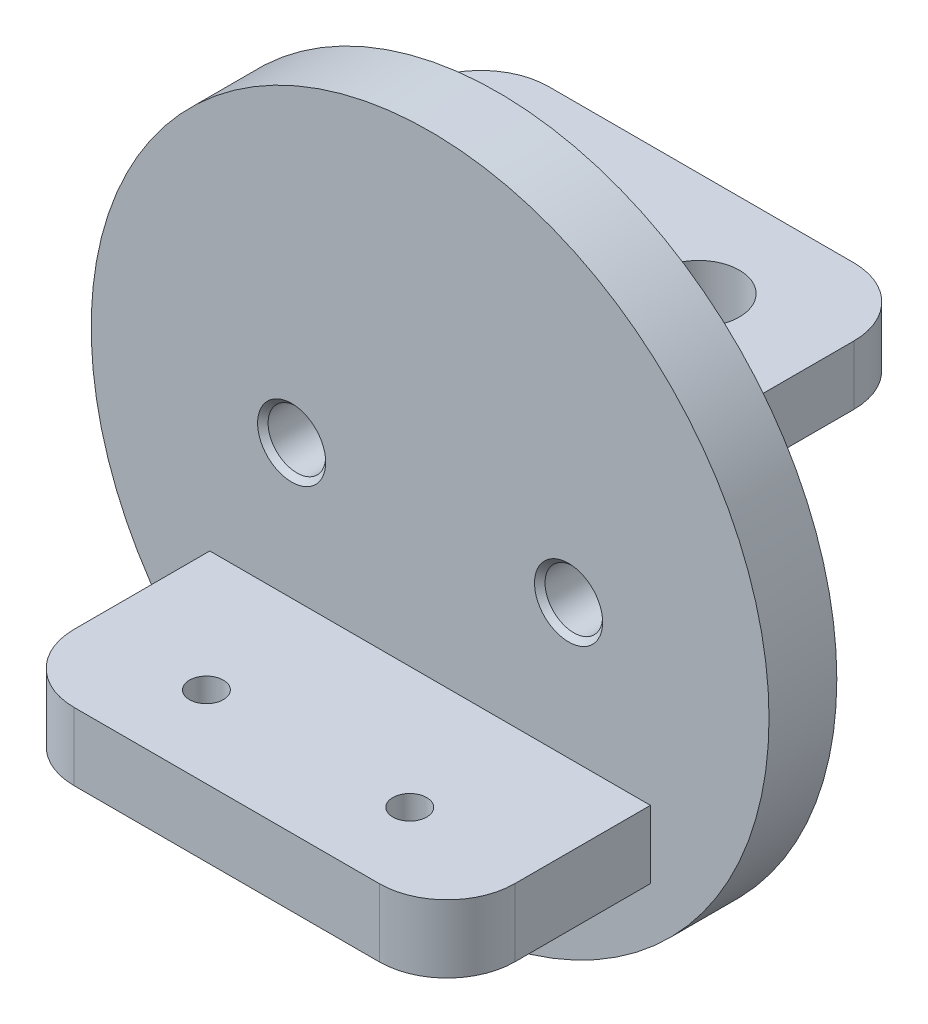
SolidWorks part; units mm, degrees
ref_plane "前视基准面" through (0, 0, 0) normal (0, 0, 1) x (1, 0, 0)
ref_plane "上视基准面" through (0, 0, 0) normal (0, 1, 0) x (1, 0, 0)
ref_plane "右视基准面" through (0, 0, 0) normal (1, 0, 0) x (0, 0, -1)
sketch "草图1" plane through (0, 0, 0) normal (0, 0, 1) x (1, 0, 0)
  circle A0 centre (0, 0) radius 50
  dimension "D1" = 100
extrude "凸台-拉伸1" add sketch "草图1" along normal blind 10
hole_wizard "M10 螺纹孔1" positions "草图7" profile "草图8" tap size "M10" standard "GB" end condition through all
sketch "草图7" plane through (0, 0, 10) normal (0, 0, 1) x (1, 0, 0)
  point P0 (-20.4267, 0)
sketch "草图8" plane through (-20.4267, 0, 10) normal (1, 0, 0) x (0, -1, 0)
  line L0 (0, 0) -> (0, 10)
  line L1 (0, 10) -> (4.25, 10)
  line L2 (4.25, 10) -> (4.25, 0.775)
  line L3 (4.25, 0.775) -> (5.025, 0)
  line L5 (5.025, 0) -> (0, 0)
  line L6 (-4.25, 0.775) -> (-5.025, 0) construction
  line L11 (0, -6.35) -> (0, 107.95) construction
  dimension "通孔螺纹孔钻头直径" = 8.5
  dimension "通孔螺纹孔钻头深度" = 10
  dimension "近端锥形沉头孔直径" = 10.05
  dimension "近端锥形沉头孔角度" = 90
cosmetic thread "孔螺蚊线1" parameters "D2"=10
mirror "镜向2" about plane through (0, 0, 0) normal (1, 0, 0) of "M10 螺纹孔1"
cosmetic thread "孔螺蚊线2" parameters "D2"=10
sketch "草图16" plane through (0, 0, 10) normal (0, 0, 1) x (1, 0, 0)
  line L0 (-32.5, -29.8649) -> (32.5, -29.8649)
  line L5 (-32.5, -29.8649) -> (32.5, 29.8649) construction
  line L6 (-32.5, 29.8649) -> (32.5, -29.8649) construction
  line L7 (-82.8685, 7.8026) -> (-82.0717, 7.2067)
  line L8 (32.5, -29.8649) -> (32.5, -19.8649)
  line L9 (-32.5, -29.8649) -> (-32.5, -19.8649)
  line L10 (-32.5, -19.8649) -> (32.5, -19.8649)
  line L17 (-32.5, 29.8649) -> (32.5, 29.8649)
  line L18 (32.5, 29.8649) -> (32.5, 19.8649)
  line L19 (-32.5, 29.8649) -> (-32.5, 19.8649)
  line L20 (-32.5, 19.8649) -> (32.5, 19.8649)
  point P0 (0, 0)
  dimension "D1" = 65
  dimension "D2" = 10
  dimension "D3" = 10
extrude "凸台-拉伸2" add sketch "草图16" along normal blind 30 contours L10 L9 L0 L8
sketch "草图18" plane through (0, 0, 10) normal (0, 0, 1) x (1, 0, 0)
  line L0 (-32.5, 24.4567) -> (-32.5, 15.7062)
  line L1 (-32.5, 15.7062) -> (32.5, 15.7062)
  line L2 (-32.5, 24.4567) -> (32.5, 24.4567)
  line L3 (32.5, 24.4567) -> (32.5, 15.7062)
  line L4 (-32.5, -29.8649) -> (-32.5, -19.8649) construction
  point P6 (-96.1204, 31.2134)
  dimension "D1" = 65
  dimension "D2" = 8.7505
extrude "凸台-拉伸3" add sketch "草图18" against normal blind 40
fillet "圆角2" radius 10 2 edges at (32.5, -24.8649, 40) (-32.5, -24.8649, 40)
fillet "圆角3" radius 10 2 edges at (32.5, 20.0814, -30) (-32.5, 20.0814, -30)
sketch "草图20" plane through (0, -29.8649, 0) normal (0, -1, 0) x (1, 0, 0)
  line L0 (0, 0) -> (0, 42.4229) construction
  line L1 (-22.5, 40) -> (22.5, 40) construction
  circle A0 centre (-15, 28) radius 2.5
  circle A1 centre (15, 28) radius 2.5
  dimension "D1" = 12
  dimension "D4" = 5
  dimension "D2" = 42.4229
  dimension "D3" = 15
extrude "切除-拉伸1" cut sketch "草图20" against normal up to next
sketch "草图22" plane through (0, 24.4567, 0) normal (0, 1, 0) x (1, 0, 0)
  line L0 (0, 0) -> (0, 30) construction
  line L1 (22.5, 30) -> (-22.5, 30) construction
  circle A0 centre (-15, 14.6157) radius 6
  circle A1 centre (15, 14.6157) radius 6
  dimension "D1" = 30
extrude "切除-拉伸2" cut sketch "草图22" against normal up to next
